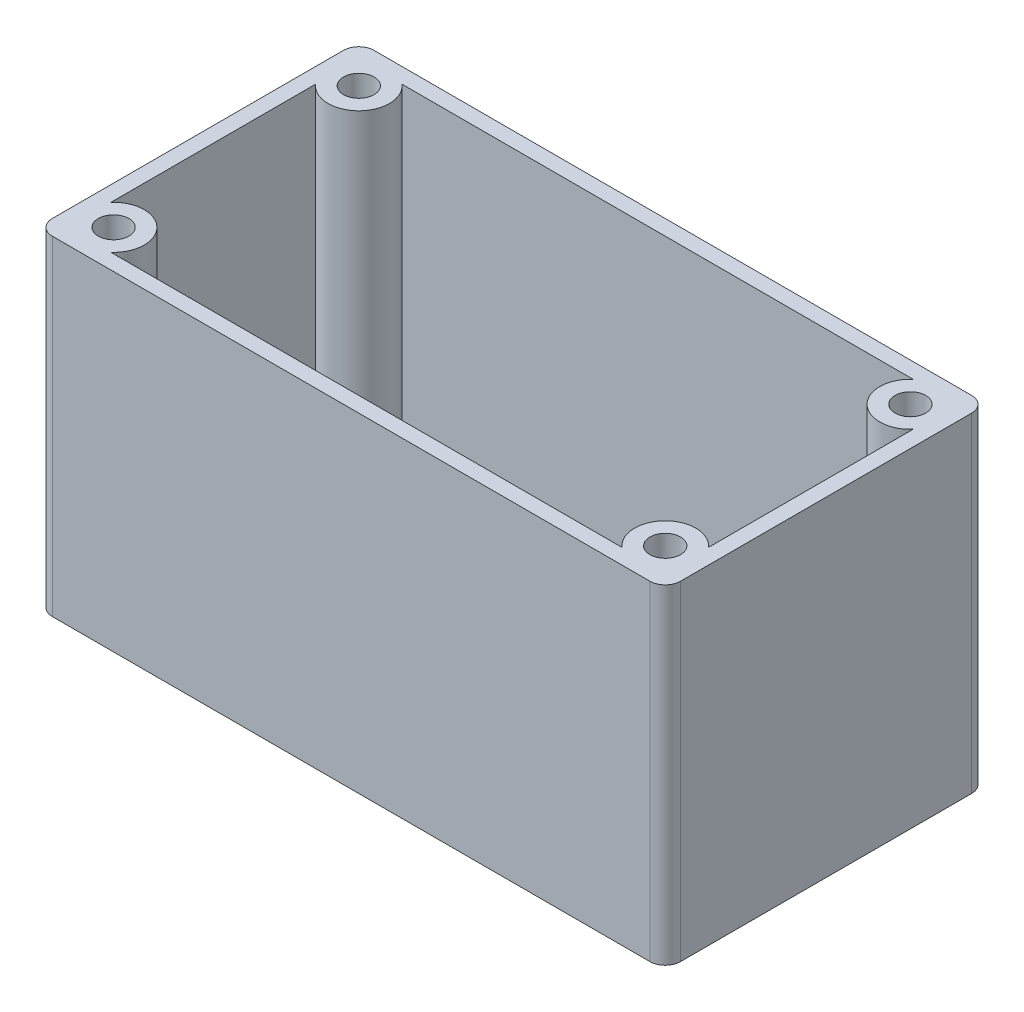
SolidWorks part; units mm, degrees
ref_plane "Plan de face" through (0, 0, 0) normal (0, 0, 1) x (1, 0, 0)
ref_plane "Plan de dessus" through (0, 0, 0) normal (0, 1, 0) x (1, 0, 0)
ref_plane "Plan de droite" through (0, 0, 0) normal (1, 0, 0) x (0, 0, -1)
sketch "Esquisse1" plane through (0, 0, 0) normal (0, 1, 0) x (1, 0, 0)
  line L0 (3.8229, 20) -> (37.1771, 20)
  line L1 (1, 0) -> (40, 0)
  line L2 (0, 1) -> (0, 20)
  line L3 (1, 21) -> (40, 21)
  line L4 (41, 1) -> (41, 20)
  line L8 (1, 20) -> (40, 20) construction
  line L9 (1, 1) -> (1, 20) construction
  line L10 (3.8229, 1) -> (37.1771, 1)
  line L11 (1, 1) -> (40, 1) construction
  line L12 (1, 3.8229) -> (1, 17.1771)
  line L13 (40, 3.8229) -> (40, 17.1771)
  line L14 (40, 1) -> (40, 20) construction
  arc A0 (0, 20) -> (1, 21) centre (1, 20) cw
  arc A1 (1, 0) -> (0, 1) centre (1, 1) cw
  arc A2 (40, 0) -> (41, 1) centre (40, 1) ccw
  arc A3 (40, 21) -> (41, 20) centre (40, 20) cw
  circle A4 centre (2.5, 18.5) radius 1
  circle A5 centre (38.5, 18.5) radius 1
  circle A6 centre (38.5, 2.5) radius 1
  circle A7 centre (2.5, 2.5) radius 1
  arc A8 (1, 17.1771) -> (3.8229, 20) centre (2.5, 18.5) ccw
  arc A9 (3.8229, 1) -> (1, 3.8229) centre (2.5, 2.5) ccw
  arc A10 (40, 3.8229) -> (37.1771, 1) centre (38.5, 2.5) ccw
  circle A16 centre (2.5, 18.5) radius 2 construction
  circle A17 centre (2.5, 2.5) radius 2 construction
  circle A19 centre (38.5, 2.5) radius 2 construction
  arc A20 (37.1771, 20) -> (40, 17.1771) centre (38.5, 18.5) ccw
  arc A21 (1, 20) -> (1, 20) centre (1, 20) cw construction
  arc A22 (40, 20) -> (40, 20) centre (40, 20) cw construction
  arc A23 (40, 1) -> (40, 1) centre (40, 1) ccw construction
  arc A24 (1, 1) -> (1, 1) centre (1, 1) cw construction
  point P7 (0, 21)
  point P10 (0, 0)
  point P15 (41, 21)
  dimension "D3" = 1
  dimension "D4" = 2
  dimension "D1" = 41
  dimension "D2" = 21
  dimension "D5" = 2.5
  dimension "D6" = 2.5
  dimension "D9" = 1
  dimension "D10" = 1
  dimension "D12" = 1
  dimension "D7" = 2
  dimension "D8" = 2
extrude "Boss.-Extru.1" add sketch "Esquisse1" along normal blind 21.5
